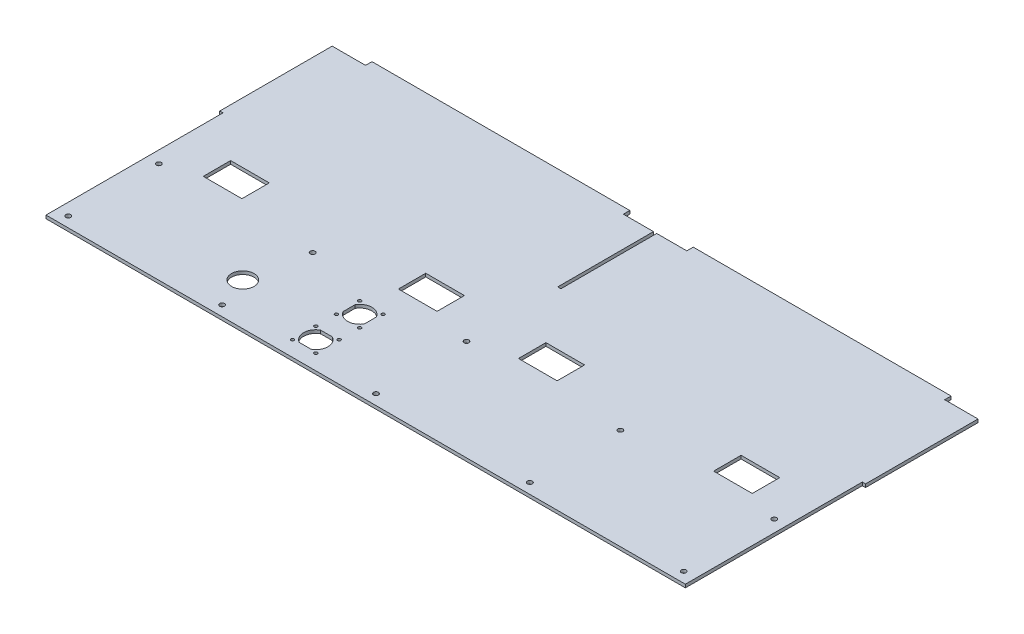
SolidWorks part; units mm, degrees
material "6061-T6 (SS)"
ref_plane "X-Y Datum" through (0, 0, 0) normal (0, 0, 1) x (1, 0, 0)
ref_plane "X-Z Datum" through (0, 0, 0) normal (0, 1, 0) x (1, 0, 0)
ref_plane "Y-Z Datum" through (0, 0, 0) normal (1, 0, 0) x (0, 0, -1)
sketch "Sketch1" plane through (0, 0, 0) normal (0, 1, 0) x (1, 0, 0)
  line L1 (0, 0) -> (629.9098, 0)
  line L2 (0, 0) -> (0, 147.6985)
  line L3 (0, 147.6985) -> (629.9098, 147.6985)
  line L4 (629.9098, 0) -> (629.9098, 147.6985)
extrude "Boss-Extrude1" add sketch "Sketch1" along normal blind 3.175
sketch "Sketch3" plane through (0, 0, -147.6985) normal (0, 0, -1) x (-1, 0, 0)
  line L0 (-629.9098, 0) -> (0, 0) construction
  line L1 (-629.9098, 0) -> (-629.9098, 3.175) construction
  line L2 (-629.9098, 3.175) -> (0, 3.175) construction
  line L3 (0, 0) -> (0, 3.175) construction
  line L4 (-600.2261, 0) -> (-346.2261, 0)
  line L5 (-600.2261, 0) -> (-600.2261, 3.175)
  line L6 (-600.2261, 3.175) -> (-346.2261, 3.175)
  line L7 (-346.2261, 0) -> (-346.2261, 3.175)
  line L8 (-283.6837, 0) -> (-29.6837, 0)
  line L9 (-283.6837, 0) -> (-283.6837, 3.175)
  line L10 (-283.6837, 3.175) -> (-29.6837, 3.175)
  line L11 (-29.6837, 0) -> (-29.6837, 3.175)
extrude "Boss-Extrude2" add sketch "Sketch3" along normal blind 6.35
sketch "Sketch4" plane through (0, 3.175, 0) normal (0, 1, 0) x (1, 0, 0)
  line L0 (346.2261, 147.6985) -> (283.6837, 147.6985) construction
  line L1 (313.3674, 53.332) -> (316.5424, 53.332)
  line L2 (313.3674, 53.332) -> (313.3674, 242.0649)
  line L3 (313.3674, 242.0649) -> (316.5424, 242.0649)
  line L4 (316.5424, 53.332) -> (316.5424, 242.0649)
  line L5 (313.3674, 53.332) -> (316.5424, 242.0649) construction
  line L6 (313.3674, 242.0649) -> (316.5424, 53.332) construction
  point P0 (314.9549, 147.6985)
extrude "Cut-Extrude1" cut sketch "Sketch4" against normal blind 3.175
sketch "Sketch6" plane through (0, 3.175, 0) normal (0, 1, 0) x (1, 0, 0)
  line L0 (314.9549, 53.332) -> (314.9549, 202.815) construction
  line L6 (629.9098, 36.9246) -> (633.0848, 36.9246)
  line L7 (633.0848, 147.6985) -> (633.0848, 36.9246)
  line L8 (629.9098, 147.6985) -> (633.0848, 147.6985)
  line L9 (629.9098, 147.6985) -> (629.9098, 36.9246)
  line L10 (0, 147.6985) -> (0, 36.9246)
  line L11 (0, 147.6985) -> (-3.175, 147.6985)
  line L12 (-3.175, 147.6985) -> (-3.175, 36.9246)
  line L13 (0, 36.9246) -> (-3.175, 36.9246)
extrude "Boss-Extrude4" add sketch "Sketch6" against normal blind 3.175
sketch "Sketch8" plane through (0, 3.175, 0) normal (0, 1, 0) x (1, 0, 0)
  line L1 (0, 0) -> (629.9098, 0)
  line L2 (0, 0) -> (0, -18.0442)
  line L3 (0, -18.0442) -> (629.9098, -18.0442)
  line L4 (629.9098, 0) -> (629.9098, -18.0442)
extrude "Boss-Extrude5" add sketch "Sketch8" against normal through all
sketch "Sketch9" plane through (0, 3.175, 0) normal (0, 1, 0) x (1, 0, 0)
  line L0 (0, -18.0442) -> (47.8104, -18.0442) construction
  line L1 (0, -18.0442) -> (629.9098, -18.0442) construction
  line L2 (314.9549, -18.0442) -> (314.9549, 180.2876) construction
  line L3 (30.0304, -36.0782) -> (65.5904, -36.0782)
  line L4 (30.0304, -36.0782) -> (30.0304, -0.0102)
  line L5 (30.0304, -0.0102) -> (65.5904, -0.0102)
  line L6 (65.5904, -36.0782) -> (65.5904, -0.0102)
  line L7 (30.0304, -36.0782) -> (65.5904, -0.0102) construction
  line L8 (30.0304, -0.0102) -> (65.5904, -36.0782) construction
  line L9 (599.8794, -0.0102) -> (564.3194, -0.0102)
  line L10 (564.3194, -36.0782) -> (564.3194, -0.0102)
  line L11 (599.8794, -36.0782) -> (564.3194, -36.0782)
  line L12 (599.8794, -36.0782) -> (599.8794, -0.0102)
extrude "Cut-Extrude2" [suppressed] cut sketch "Sketch9" against normal through all
sketch "Sketch10" plane through (0, 3.175, 0) normal (0, 1, 0) x (1, 0, 0)
  line L0 (313.3674, 53.332) -> (313.3674, -18.0442) construction
  line L1 (314.9549, -18.0442) -> (314.9549, -25.2417) construction
  line L2 (0, -18.0442) -> (629.9098, -18.0442) construction
  line L3 (313.3674, -18.0442) -> (274.7924, -18.0442) construction
  line L4 (355.1174, 0) -> (393.2174, 0)
  line L5 (274.7924, -18.0442) -> (236.6924, -18.0442)
  line L6 (274.7924, -18.0442) -> (274.7924, 0)
  line L7 (274.7924, 0) -> (236.6924, 0)
  line L8 (236.6924, -18.0442) -> (236.6924, 0)
  line L9 (393.2174, -18.0442) -> (393.2174, 0)
  line L10 (355.1174, -18.0442) -> (393.2174, -18.0442)
  line L11 (355.1174, -18.0442) -> (355.1174, 0)
  line L12 (0, -18.0442) -> (63.5, -18.0442) construction
  line L13 (0, -18.0442) -> (629.9098, -18.0442) construction
  line L22 (585.4598, 0) -> (547.3598, 0)
  line L23 (44.45, -36.0883) -> (82.55, -36.0883)
  line L24 (44.45, -36.0883) -> (44.45, 0)
  line L25 (44.45, 0) -> (82.55, 0)
  line L26 (82.55, -36.0883) -> (82.55, 0)
  line L27 (44.45, -36.0883) -> (82.55, 0) construction
  line L28 (44.45, 0) -> (82.55, -36.0883) construction
  line L29 (547.3598, -36.0883) -> (547.3598, 0)
  line L30 (585.4598, -36.0883) -> (547.3598, -36.0883)
  line L31 (585.4598, -36.0883) -> (585.4598, 0)
  dimension "D1" = 38.575
  dimension "D2" = 38.1
extrude "Cut-Extrude3" cut sketch "Sketch10" against normal through all
sketch "Sketch11" plane through (0, 3.175, 0) normal (0, 1, 0) x (1, 0, 0)
  line L0 (274.7924, -18.0442) -> (355.1174, -18.0442) construction
  line L2 (0, -18.0442) -> (0, -137.4242)
  line L3 (0, -137.4242) -> (629.9098, -137.4242)
  line L4 (629.9098, -18.0442) -> (629.9098, -137.4242)
  line L5 (314.9549, -18.0442) -> (629.9098, -137.4242) construction
  line L6 (0, -137.4242) -> (314.9549, -18.0442) construction
  line L7 (0, -18.0442) -> (44.45, -18.0442)
  line L8 (274.7924, -18.0442) -> (355.1174, -18.0442)
  line L10 (236.6924, -18.0442) -> (236.6924, -26.9519)
  line L11 (236.6924, -26.9519) -> (274.7924, -26.9519)
  line L12 (274.7924, -18.0442) -> (274.7924, -26.9519)
  line L14 (355.1174, -18.0442) -> (355.1174, -27.0662)
  line L15 (355.1174, -27.0662) -> (393.2174, -27.0662)
  line L16 (393.2174, -18.0442) -> (393.2174, -27.0662)
  line L17 (393.2174, -18.0442) -> (547.3598, -18.0442)
  line L18 (44.45, -18.0442) -> (44.45, -26.9519)
  line L19 (44.45, -26.9519) -> (82.55, -26.9519)
  line L20 (82.55, -26.9519) -> (82.55, -18.0442)
  line L21 (547.3598, -18.0442) -> (547.3598, -27.0662)
  line L22 (547.3598, -27.0662) -> (585.4598, -27.0662)
  line L23 (585.4598, -27.0662) -> (585.4598, -18.0442)
  line L24 (82.55, -18.0442) -> (236.6924, -18.0442)
  line L25 (585.4598, -18.0442) -> (629.9098, -18.0442)
  point P0 (314.9549, -18.0442)
extrude "Boss-Extrude6" add sketch "Sketch11" against normal through all
sketch "Sketch12" [suppressed] plane through (0, 3.175, 0) normal (0, 1, 0) x (1, 0, 0)
  line L1 (44.45, 0) -> (82.55, 0)
  line L2 (44.45, 0) -> (44.45, -18.0442)
  line L3 (44.45, -18.0442) -> (82.55, -18.0442)
  line L4 (82.55, 0) -> (82.55, -18.0442)
  line L5 (547.3598, 0) -> (585.4598, 0)
  line L6 (547.3598, 0) -> (547.3598, -18.0442)
  line L7 (547.3598, -18.0442) -> (585.4598, -18.0442)
  line L8 (585.4598, 0) -> (585.4598, -18.0442)
extrude "Boss-Extrude7" [suppressed] add sketch "Sketch12" against normal through all
sketch "Sketch13" plane through (0, 0, 0) normal (0, -1, 0) x (1, 0, 0)
  line L0 (244.9105, 120.8318) -> (233.5527, 120.8318) construction
  line L1 (244.9105, 100.8318) -> (233.5527, 100.8318) construction
  line L2 (249.2316, 73.2621) -> (249.2316, 61.9043) construction
  line L3 (229.2316, 73.2621) -> (229.2316, 61.9043) construction
  line L4 (245.0431, 100.3238) -> (233.42, 100.3238)
  line L5 (245.0431, 121.3398) -> (233.42, 121.3398)
  line L6 (249.7396, 73.3947) -> (249.7396, 61.7716)
  line L7 (228.7236, 73.3947) -> (228.7236, 61.7716)
  line L8 (2.2083, 136.32) -> (632.1181, 136.32) construction
  line L9 (2.2083, 136.32) -> (2.2083, 49.1456) construction
  line L10 (2.2083, 49.1456) -> (632.1181, 49.1456) construction
  line L11 (632.1181, 136.32) -> (632.1181, 49.1456) construction
  circle A0 centre (227.7316, 122.3318) radius 1.55
  circle A1 centre (250.7316, 122.3318) radius 1.55
  circle A2 centre (227.7316, 99.3318) radius 1.55
  circle A3 centre (250.7316, 99.3318) radius 1.55
  circle A4 centre (152.3285, 95.8779) radius 11.049
  circle A5 centre (227.7316, 79.0832) radius 1.55
  circle A6 centre (227.7316, 56.0832) radius 1.55
  circle A7 centre (250.7316, 56.0832) radius 1.55
  circle A8 centre (250.7316, 79.0832) radius 1.55
  arc A9 (249.2316, 73.2621) -> (229.2316, 73.2621) centre (239.2316, 67.5832) ccw construction
  arc A10 (249.2316, 61.9043) -> (229.2316, 61.9043) centre (239.2316, 67.5832) cw construction
  arc A11 (244.9105, 120.8318) -> (244.9105, 100.8318) centre (239.2316, 110.8318) cw construction
  arc A12 (233.5527, 120.8318) -> (233.5527, 100.8318) centre (239.2316, 110.8318) ccw construction
  arc A13 (233.42, 121.3398) -> (233.42, 100.3238) centre (239.2316, 110.8318) ccw
  arc A14 (245.0431, 121.3398) -> (245.0431, 100.3238) centre (239.2316, 110.8318) cw
  arc A15 (249.7396, 61.7716) -> (228.7236, 61.7716) centre (239.2316, 67.5832) cw
  arc A16 (249.7396, 73.3947) -> (228.7236, 73.3947) centre (239.2316, 67.5832) ccw
extrude "Cut-Extrude4" cut sketch "Sketch13" against normal through all
sketch "Sketch14" plane through (0, 0, 0) normal (0, -1, 0) x (1, 0, 0)
  line L0 (0, 137.4242) -> (653.3937, 137.4242) construction
  line L1 (0, 137.4242) -> (0, -17.9044) construction
  line L2 (0, -17.9044) -> (653.3937, -17.9044) construction
  line L3 (653.3937, 137.4242) -> (653.3937, -17.9044) construction
  point P0 (11.811, 127.2642)
  point P1 (163.383, 127.2642)
  point P2 (314.9549, 127.2642)
  point P3 (466.5269, 127.2642)
  point P4 (618.0988, 127.2642)
  point P5 (618.0988, 38.1102)
  point P6 (466.5269, 38.1102)
  point P7 (314.9549, 38.1102)
  point P8 (163.383, 38.1102)
  point P9 (11.811, 38.1102)
hole_wizard "M4 Clearance Hole1" positions "Sketch15" profile "Sketch16" hole size "M4" standard "ANSI Metric" end condition through all
sketch "Sketch15" plane through (0, 0, 0) normal (0, -1, 0) x (-1, 0, 0)
  point P0 (-618.0988, -38.1102)
  point P3 (-466.5269, -38.1102)
  point P6 (-618.0988, -127.2642)
  point P9 (-466.5269, -127.2642)
  point P12 (-314.9549, -127.2642)
  point P15 (-314.9549, -38.1102)
  point P18 (-163.383, -38.1102)
  point P21 (-11.811, -38.1102)
  point P24 (-11.811, -127.2642)
  point P27 (-163.383, -127.2642)
sketch "Sketch16" plane through (618.0988, 0, 38.1102) normal (1, 0, 0) x (0, 0, -1)
  line L0 (0, 0) -> (0, 3.175)
  line L1 (0, 3.175) -> (2.4, 3.175)
  line L2 (2.4, 3.175) -> (2.4, 0)
  line L5 (2.4, 0) -> (0, 0)
  line L11 (0, -6.35) -> (0, 107.95) construction
  dimension "Thru Hole Dia." = 4.8
  dimension "Thru Hole Depth" = 3.175
